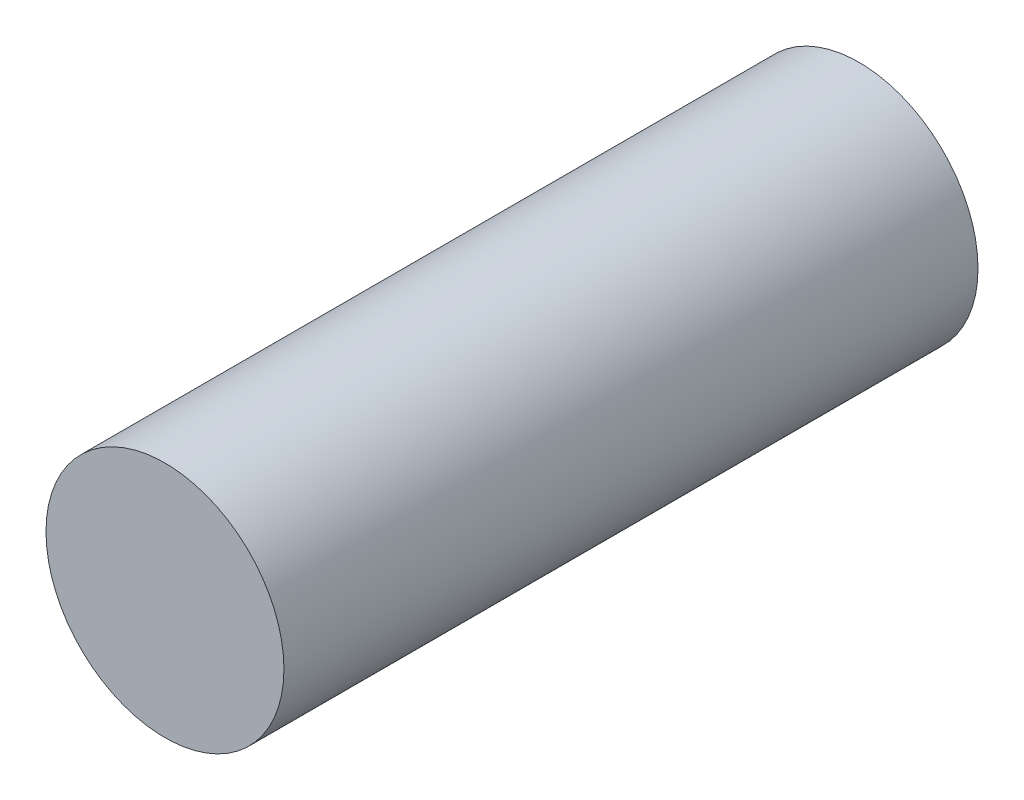
SolidWorks part; units mm, degrees
ref_plane "Front Plane" through (0, 0, 0) normal (0, 0, 1) x (1, 0, 0)
ref_plane "Top Plane" through (0, 0, 0) normal (0, 1, 0) x (1, 0, 0)
ref_plane "Right Plane" through (0, 0, 0) normal (1, 0, 0) x (0, 0, -1)
sketch "Sketch1" plane through (0, 0, 0) normal (0, 0, 1) x (1, 0, 0)
  circle A0 centre (0, 0) radius 6
  dimension "D1" = 12
extrude "Boss-Extrude1" add sketch "Sketch1" along normal blind 35
